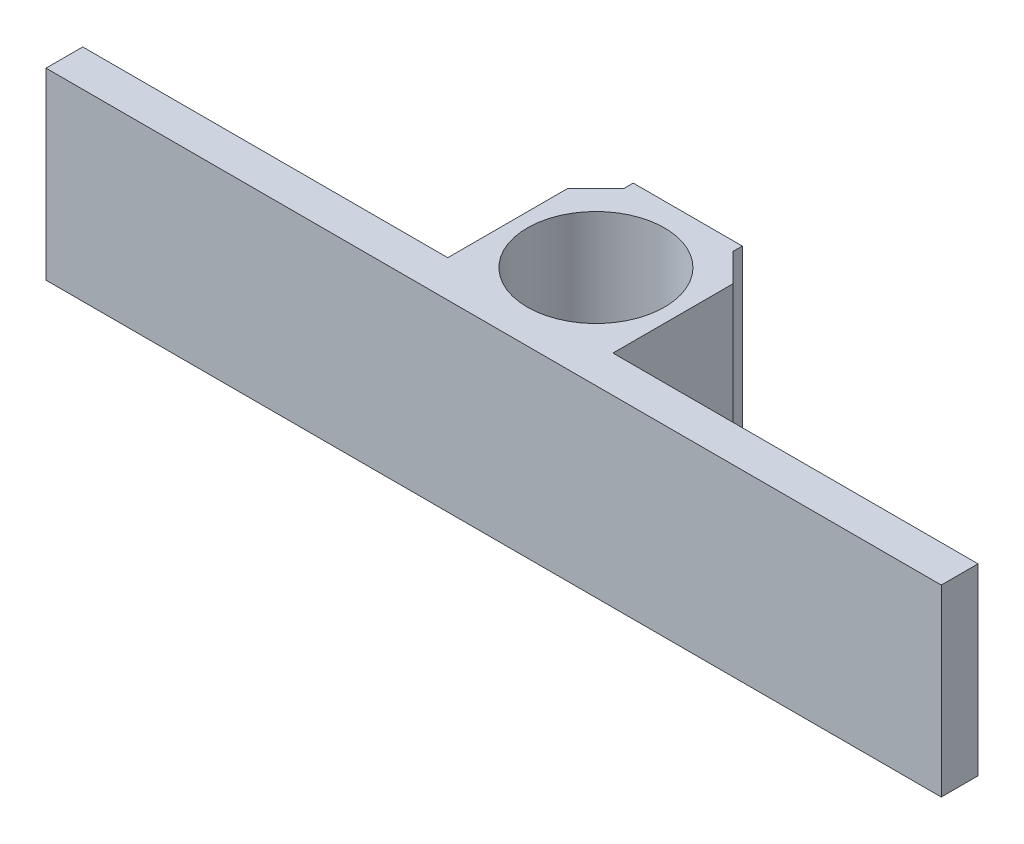
SolidWorks part; units mm, degrees
ref_plane "Front Plane" through (0, 0, 0) normal (0, 0, 1) x (1, 0, 0)
ref_plane "Top Plane" through (0, 0, 0) normal (0, 1, 0) x (1, 0, 0)
ref_plane "Right Plane" through (0, 0, 0) normal (1, 0, 0) x (0, 0, -1)
sketch "Sketch1" plane through (0, 0, 0) normal (0, 0, 1) x (1, 0, 0)
  line L1 (-151.2906, 21.747) -> (96.3594, 21.747)
  line L2 (-151.2906, 21.747) -> (-151.2906, -29.053)
  line L3 (-151.2906, -29.053) -> (96.3594, -29.053)
  line L4 (96.3594, 21.747) -> (96.3594, -29.053)
  dimension "D1" = 247.65
  dimension "D2" = 50.8
extrude "Boss-Extrude1" add sketch "Sketch1" along normal blind 10.16
sketch "Sketch5" plane through (0, 21.747, 0) normal (0, 1, 0) x (1, 0, 0)
  line L0 (-20.8616, 0) -> (-20.8616, -10.16)
  line L1 (96.3594, 0) -> (-151.2906, 0) construction
  line L2 (96.3594, -10.16) -> (-151.2906, -10.16) construction
  line L3 (-34.0696, 0) -> (-34.0696, -10.16)
  point P8 (-27.4656, 0)
  dimension "D1" = 6.604
  dimension "D2" = 6.604
sketch "Sketch6" plane through (0, 21.747, 0) normal (0, 1, 0) x (1, 0, 0)
  arc A0 (-20.8616, 0) -> (-34.0696, 0) centre (-27.4656, 10.8827) cw
extrude "Cut-Extrude1" cut sketch "Sketch6" against normal through all and the other way through all flip side to cut
sketch "Sketch7" plane through (0, 21.747, 0) normal (0, 1, 0) x (1, 0, 0)
  line L0 (-27.4656, -4.7215) -> (-27.4643, 18.1385)
  line L1 (96.3594, -10.16) -> (96.3594, 0) construction
  circle A1 centre (-27.4643, 18.1385) radius 22.8473
  point P2 (0, 0)
  point P3 (0, 0)
  dimension "D1" = 22.86
  dimension "D2" = 123.825
extrude "Boss-Extrude2" add sketch "Sketch7" against normal through all contours A1
sketch "Sketch8" plane through (0, 21.747, 0) normal (0, 1, 0) x (1, 0, 0)
  circle A0 centre (-27.4643, 18.1385) radius 18.9865
  dimension "D1" = 37.973
extrude "Cut-Extrude2" cut sketch "Sketch8" against normal blind 45.72
sketch "Sketch9" plane through (0, -23.973, 0) normal (0, 1, 0) x (1, 0, 0)
  circle A0 centre (-27.4643, 18.1385) radius 7.9375
  circle A1 centre (-27.4643, 18.1385) radius 18.9865 construction
  dimension "D1" = 15.875
  dimension "D2" = 0
extrude "Cut-Extrude3" cut sketch "Sketch9" against normal through all
sketch "Sketch12" plane through (0, 21.747, 0) normal (0, 1, 0) x (1, 0, 0)
  line L0 (-4.617, 18.1385) -> (-4.617, 0)
  line L1 (96.3594, 0) -> (-13.5721, 0) construction
  line L2 (-4.617, 0) -> (-13.5721, 0)
  line L3 (-50.3115, 18.1385) -> (-50.3115, 0)
  line L4 (-41.3564, 0) -> (-151.2906, 0) construction
  line L5 (-50.3115, 0) -> (-41.3564, 0)
  circle A0 centre (-27.4643, 18.1385) radius 22.8473 construction
  arc A1 (-13.5721, 0) -> (-4.617, 18.1385) centre (-27.4643, 18.1385) ccw
  arc A2 (-41.3564, 0) -> (-50.3115, 18.1385) centre (-27.4643, 18.1385) cw
  point P16 (-50.3115, 18.1385)
extrude "Boss-Extrude3" add sketch "Sketch12" against normal up to surface (50.8 mm away) up to face at (-27.4643, -29.053, -10.201)
sketch "Sketch16" plane through (0, -29.053, 0) normal (0, -1, 0) x (1, 0, 0)
  line L0 (-50.3115, -18.1385) -> (-50.3115, -40.9857)
  line L1 (-27.4643, -40.9857) -> (-50.3115, -40.9857)
  arc A0 (-50.3115, -18.1385) -> (-4.617, -18.1385) centre (-27.4643, -18.1385) ccw construction
  arc A1 (-50.3115, -18.1385) -> (-27.4643, -40.9857) centre (-27.4643, -18.1385) ccw
extrude "Boss-Extrude4" add sketch "Sketch16" against normal up to surface (50.8 mm away) up to face at (-27.4649, 21.747, -4.8505)
sketch "Sketch18" plane through (0, -29.053, 0) normal (0, -1, 0) x (1, 0, 0)
  line L0 (-4.617, -18.1385) -> (-4.617, -40.9857)
  line L1 (-4.617, -40.9857) -> (-27.4643, -40.9857)
  arc A0 (-4.617, -18.1385) -> (-27.4643, -40.9857) centre (-27.4643, -18.1385) cw
extrude "Boss-Extrude5" add sketch "Sketch18" against normal up to surface (50.8 mm away) up to face at (-26.9391, 21.747, -9.3913)
sketch "Sketch22" plane through (0, 0, -40.9857) normal (0, 0, -1) x (-1, 0, 0)
  line L0 (4.617, 21.747) -> (50.3115, 21.747) construction
  line L1 (42.5328, 21.747) -> (12.3703, 21.747)
  line L2 (42.5328, 21.747) -> (42.5328, -29.053)
  line L3 (42.5328, -29.053) -> (12.3703, -29.053)
  line L4 (12.3703, 21.747) -> (12.3703, -29.053)
  line L5 (50.3115, -29.053) -> (4.617, -29.053) construction
  line L6 (50.3115, 21.747) -> (50.3115, -29.053) construction
  point P8 (27.4515, -29.053)
  dimension "D1" = 30.1625
  dimension "D2" = 22.86
extrude "Boss-Extrude6" add sketch "Sketch22" along normal blind 2.54
sketch "Sketch23" plane through (0, 21.747, 0) normal (0, 1, 0) x (1, 0, 0)
  line L0 (-42.5328, 40.9857) -> (-50.3115, 33.207)
  line L1 (-50.3115, 40.9857) -> (-50.3115, 0) construction
  line L2 (-50.3115, 33.207) -> (-50.3115, 40.9857)
  line L3 (-50.3115, 40.9857) -> (-42.5328, 40.9857)
  line L4 (-12.3703, 40.9857) -> (-4.617, 33.2325)
  line L5 (-4.617, 0) -> (-4.617, 40.9857) construction
  line L6 (-4.617, 33.2325) -> (-4.617, 40.9857)
  line L7 (-4.617, 40.9857) -> (-12.3703, 40.9857)
extrude "Cut-Extrude4" cut sketch "Sketch23" against normal through all
hole_wizard "Tap Drill for 1/4 Helicoil1" positions "Sketch26" profile "Sketch27" hole size "1/4-20" standard "ANSI Inch"
sketch "Sketch26" plane through (14.3077, 0, -14.3077) normal (0.7071, 0, -0.7071) x (-0.7071, 0, -0.7071)
  line L0 (26.7636, -29.053) -> (26.7636, 21.747) construction
  line L1 (32.246, -23.973) -> (32.246, 21.747) construction
  line L2 (40.1835, -23.973) -> (24.3085, -23.973) construction
  point P0 (32.2246, -4.9231)
  point P2 (32.246, -17.623)
  dimension "D1" = 12.7
  dimension "D2" = 5.461
  dimension "D3" = 6.35
sketch "Sketch27" plane through (-8.4785, -4.9231, -37.094) normal (0, 1, 0) x (-0.7071, 0, -0.7071)
  line L0 (0, 0) -> (0, 7.842)
  line L1 (0, 7.842) -> (3.3782, 7.842)
  line L2 (3.3782, 7.842) -> (3.3782, 0)
  line L5 (3.3782, 0) -> (0, 0)
  line L11 (0, -6.35) -> (0, 107.95) construction
  dimension "Thru Hole Dia." = 6.7564
  dimension "Thru Hole Depth" = 7.842
ref_plane "Plane2" through (8.9196, 0, -8.9196) normal (0.7071, 0, -0.7071) x (-0.7071, 0, -0.7071)
sketch "Sketch28" plane through (8.9196, 0, -8.9196) normal (0.7071, 0, -0.7071) x (-0.7071, 0, -0.7071)
  line L0 (55.0933, 21.747) -> (9.3988, 21.747) construction
  line L7 (28.9464, -23.338) -> (35.5456, -23.338)
  line L8 (35.5456, -23.338) -> (38.8451, -17.623)
  line L9 (38.8451, -17.623) -> (35.5456, -11.908)
  line L10 (35.5456, -11.908) -> (28.9464, -11.908)
  line L11 (28.9464, -11.908) -> (25.6469, -17.623)
  line L12 (25.6469, -17.623) -> (28.9464, -23.338)
  line L13 (38.8237, -4.9231) -> (35.5242, 0.7919)
  line L14 (35.5242, 0.7919) -> (28.9251, 0.7919)
  line L15 (28.9251, 0.7919) -> (25.6255, -4.9231)
  line L16 (25.6255, -4.9231) -> (28.9251, -10.6381)
  line L17 (28.9251, -10.6381) -> (35.5242, -10.6381)
  line L18 (35.5242, -10.6381) -> (38.8237, -4.9231)
  circle A1 centre (32.246, -17.623) radius 5.715 construction
  circle A2 centre (32.2246, -4.9231) radius 5.715 construction
  point P0 (32.2246, -17.623)
  point P27 (25.1106, -17.623)
  point P28 (23.6523, -4.6972)
  dimension "D1" = 11.43
extrude "Cut-Extrude5" cut sketch "Sketch28" along normal blind 5.5562 and the other way up to next
